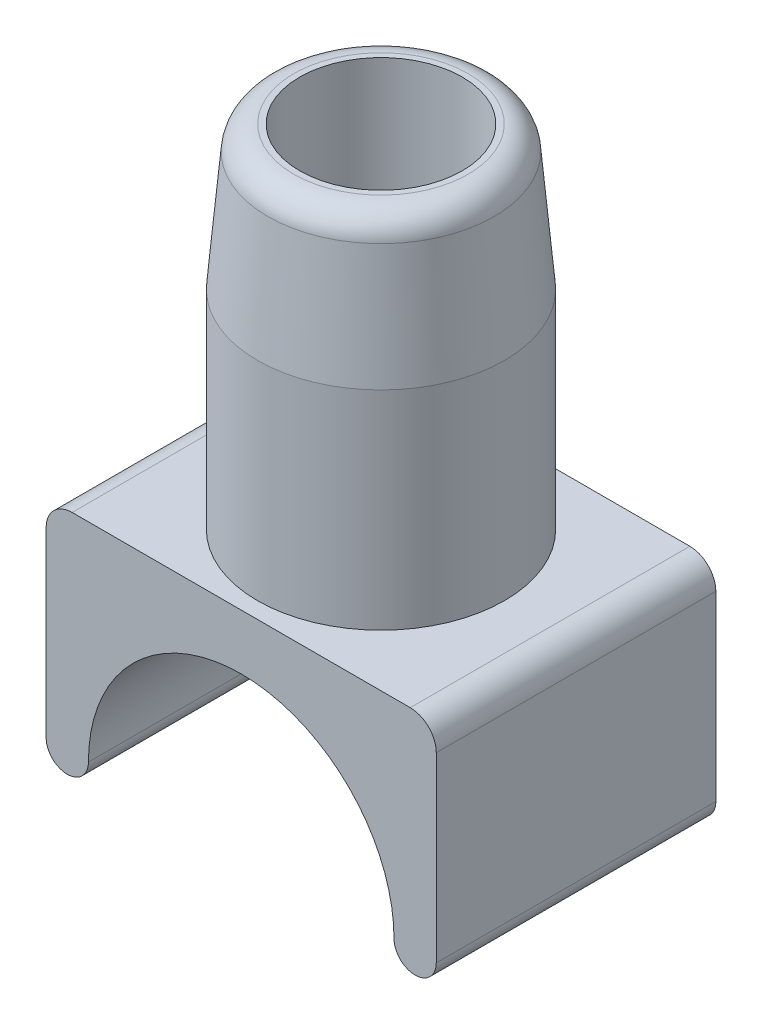
SolidWorks part; units mm, degrees
ref_plane "Front Plane" through (0, 0, 0) normal (0, 0, 1) x (1, 0, 0)
ref_plane "Top Plane" through (0, 0, 0) normal (0, 1, 0) x (1, 0, 0)
ref_plane "Right Plane" through (0, 0, 0) normal (1, 0, 0) x (0, 0, -1)
sketch "Sketch1" plane through (0, 0, 0) normal (0, 0, 1) x (1, 0, 0)
  line L0 (-13, 0) -> (13, 0)
  line L1 (15, -2) -> (15, -16)
  line L2 (15, -16) -> (11.75, -16) construction
  line L3 (-15, -16) -> (-15, -2)
  line L4 (0, 17.3487) -> (0, -38.1417) construction
  line L5 (-11.75, -16) -> (-15, -16) construction
  arc A0 (11.75, -16) -> (-11.75, -16) centre (0, -16) ccw
  arc A1 (-15, -16) -> (-11.75, -16) centre (-13.375, -16) ccw
  arc A2 (11.75, -16) -> (15, -16) centre (13.375, -16) ccw
  arc A3 (15, -2) -> (13, 0) centre (13, -2) ccw
  arc A4 (-15, -2) -> (-13, 0) centre (-13, -2) cw
  point P4 (0, 0)
  point P15 (0, 0)
  point P18 (-15, 0)
  dimension "D3" = 23.5
  dimension "D4" = 2
  dimension "D1" = 16
  dimension "D2" = 30
extrude "Boss-Extrude1" add sketch "Sketch1" along normal mid plane 21.5
sketch "Sketch3" plane through (0, 0, 0) normal (0, 0, 1) x (1, 0, 0)
  line L0 (0, 13.1861) -> (0, -14.7237) construction
  line L1 (-9.5, 0) -> (-9.5, 16)
  line L2 (13, 0) -> (-13, 0) construction
  line L3 (-9.5, 16) -> (-8.5376, 27)
  line L4 (-8.5376, 27) -> (-6.25, 27)
  line L6 (-6.25, 27) -> (-6.25, 0)
  line L7 (-6.25, 0) -> (-9.5, 0)
  point P8 (-6.25, 15)
  point P12 (-3.3207, 27)
  point P13 (-6.4088, 15)
  point P14 (0, 0)
  point P15 (-8.3996, 27)
  dimension "D1" = 19
  dimension "D2" = 12.5
  dimension "D3" = 27
  dimension "D4" = 16
  dimension "D5" = 85
revolve "Revolve1" add sketch "Sketch3" angle 360 about L0
fillet "Fillet2" radius 2 1 edges at (0, 27, 8.5376)
